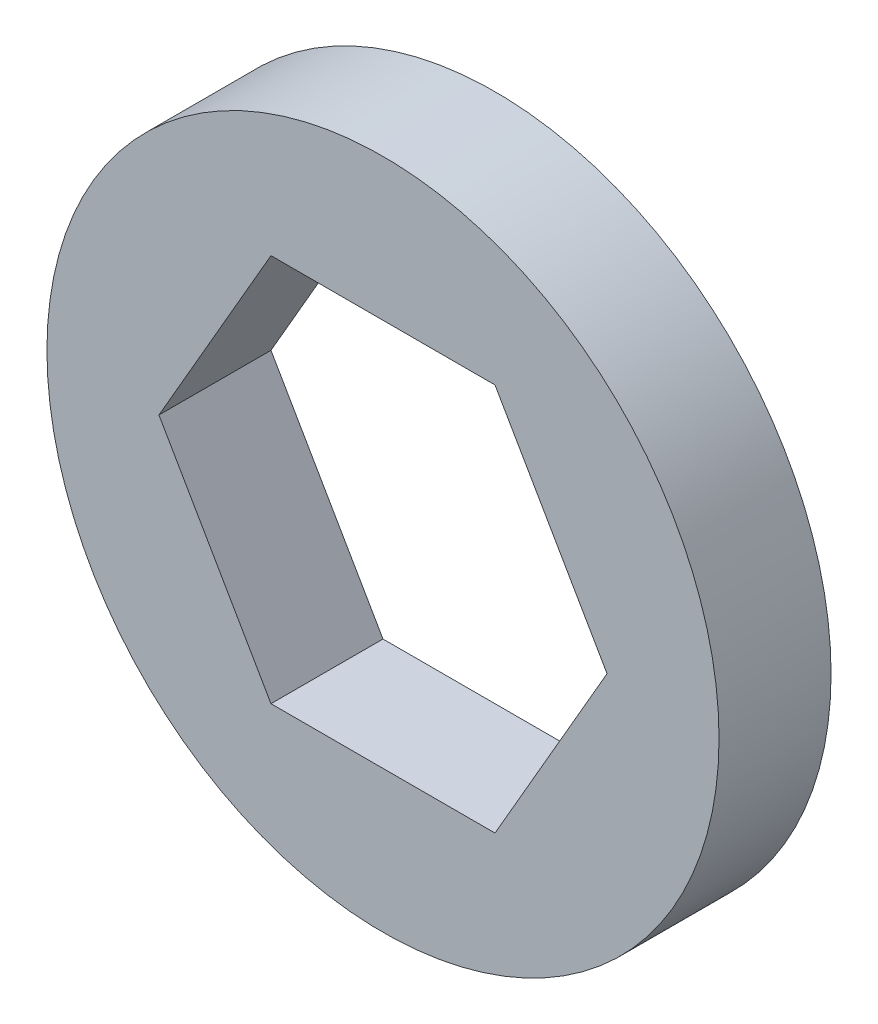
SolidWorks part; units mm, degrees
material "Nylon 101"
ref_plane "Front Plane" through (0, 0, 0) normal (0, 0, 1) x (1, 0, 0)
ref_plane "Top Plane" through (0, 0, 0) normal (0, 1, 0) x (1, 0, 0)
ref_plane "Right Plane" through (0, 0, 0) normal (1, 0, 0) x (0, 0, -1)
sketch "Sketch1" plane through (0, 0, 0) normal (0, 0, 1) x (1, 0, 0)
  line L1 (-3.175, 5.4993) -> (-6.35, 0)
  line L2 (-6.35, 0) -> (-3.175, -5.4993)
  line L3 (-3.175, -5.4993) -> (3.175, -5.4993)
  line L4 (3.175, -5.4993) -> (6.35, 0)
  line L5 (6.35, 0) -> (3.175, 5.4993)
  line L6 (3.175, 5.4993) -> (-3.175, 5.4993)
  circle A0 centre (0, 0) radius 5.4993 construction
  circle A1 centre (0, 0) radius 9.525
  point P1 (0, 5.4993)
  dimension "D2" = 19.05
  dimension "D1" = 12.7
extrude "Boss-Extrude1" add sketch "Sketch1" along normal blind 3.175
